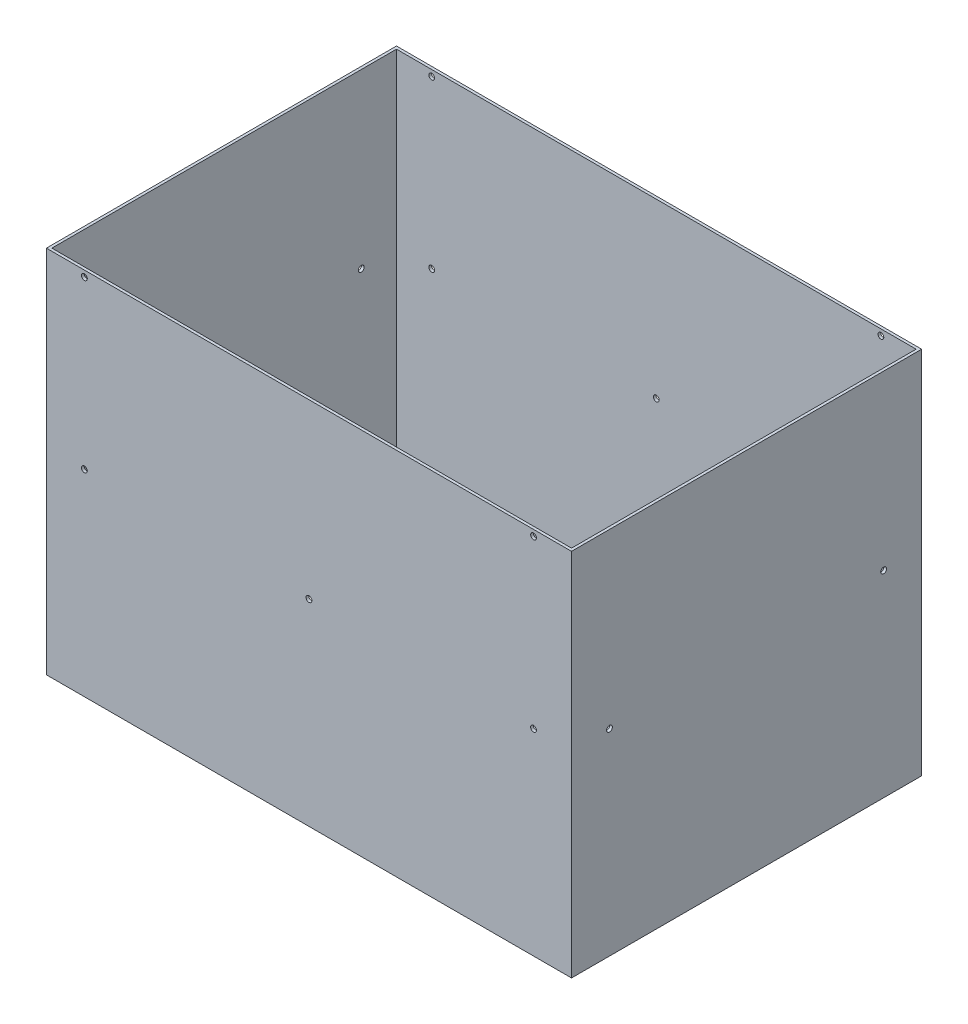
SolidWorks part; units mm, degrees
ref_plane "Alzado" through (0, 0, 0) normal (0, 0, 1) x (1, 0, 0)
ref_plane "Planta" through (0, 0, 0) normal (0, 1, 0) x (1, 0, 0)
ref_plane "Vista lateral" through (0, 0, 0) normal (1, 0, 0) x (0, 0, -1)
sketch "Croquis1" plane through (0, 0, 0) normal (0, 0, 1) x (1, 0, 0)
  line L0 (-135, -46.6) -> (135, -46.6)
  line L1 (0, -55) -> (0, 55) construction
  line L2 (-135, -46.6) -> (-135, 143.4)
  line L3 (135, -46.6) -> (135, 143.4)
  line L4 (-135, 143.4) -> (135, 143.4)
  line L9 (55, 0) -> (-55, 0) construction
  point P2 (0, -46.6)
  point P5 (-135, 0)
  dimension "D1" = 270
  dimension "D6" = 190
extrude "Saliente-Extruir1" add sketch "Croquis1" along normal mid plane 180
sketch "Croquis2" plane through (0, -46.6, 0) normal (0, 1, 0) x (1, 0, 0)
  line L0 (-55, 0) -> (55, 0) construction
  line L1 (-66, 76) -> (-66, -57)
  line L2 (-66, -57) -> (-126, -57)
  line L3 (-126, -57) -> (-126, 76)
  line L4 (-126, 76) -> (-66, 76)
  line L5 (69.26, 53) -> (69.26, -80)
  line L6 (69.26, -80) -> (129.26, -80)
  line L7 (129.26, -80) -> (129.26, 53)
  line L8 (129.26, 53) -> (69.26, 53)
  line L9 (135, 90) -> (-135, 90) construction
  line L12 (135, -90) -> (-135, -90) construction
  point P1 (67.5, 0)
  point P7 (-66, 76)
  point P9 (-66, -57)
  point P10 (69.26, -80)
  point P13 (69.26, 53)
  point P14 (-68.26, -63.8)
  dimension "D2" = 10
  dimension "D3" = 133
  dimension "D4" = 133
  dimension "D5" = 60
  dimension "D6" = 66
  dimension "D7" = 90
  dimension "D8" = 90
  dimension "D9" = 60
  dimension "D10" = 67.5
  dimension "D11" = 14
extrude "Cortar-Extruir2" cut sketch "Croquis2" against normal mid plane 71.4
sketch "Croquis6" plane through (0, 143.4, 0) normal (0, 1, 0) x (1, 0, 0)
  line L0 (135, 90) -> (-135, 90) construction
  line L1 (-133.6, 88.6) -> (133.6, 88.6)
  line L2 (-133.6, 88.6) -> (-133.6, -88.6)
  line L3 (-133.6, -88.6) -> (133.6, -88.6)
  line L4 (133.6, 88.6) -> (133.6, -88.6)
  line L5 (-135, -90) -> (-135, 90) construction
  line L6 (135, -90) -> (135, 90) construction
  line L7 (135, -90) -> (-135, -90) construction
  dimension "D1" = 1.4
  dimension "D2" = 1.4
  dimension "D3" = 1.4
  dimension "D4" = 1.4
  dimension "D5" = 177.2
extrude "Cortar-Extruir3" cut sketch "Croquis6" against normal blind 188.6
ref_plane "Plano2" through (0, 54.65, 0) normal (0, 1, 0) x (1, 0, 0)
sketch "Croquis8" plane through (0, 0, 90) normal (0, 0, 1) x (1, 0, 0)
  line L0 (123.1006, 54.65) -> (-123.1006, 54.65) construction
  line L1 (-135, 143.4) -> (-135, -46.6) construction
  line L2 (-135, 54.65) -> (135, 54.65) construction
  line L3 (135, -46.6) -> (135, 143.4) construction
  circle A0 centre (-115.475, 54.65) radius 1.5
  circle A1 centre (0, 54.65) radius 1.5
  circle A2 centre (115.475, 54.65) radius 1.5
  point P0 (-135, 54.65)
  point P5 (-135, 54.65)
  point P10 (-115.475, 54.65)
  point P11 (0, 54.65)
  point P12 (115.475, 54.65)
  dimension "D1" = 0
  dimension "D2" = 19.525
  dimension "D4" = 19.525
extrude "Cortar-Extruir4" cut sketch "Croquis8" against normal mid plane 600
sketch "Croquis10" plane through (-135, 0, 0) normal (-1, 0, 0) x (0, 0, 1)
  line L2 (90, 143.4) -> (90, -46.6) construction
  line L9 (-90, 143.4) -> (-90, -46.6) construction
  line L10 (123.1006, 54.65) -> (-123.1006, 54.65) construction
  line L11 (-90, 54.65) -> (90, 54.65) construction
  circle A0 centre (-70.475, 54.65) radius 1.5
  circle A1 centre (70.475, 54.65) radius 1.5
  point P0 (-90, 54.65)
  point P1 (-70.475, 54.65)
  point P4 (70.475, 54.65)
  dimension "D1" = 19.525
  dimension "D2" = 19.525
extrude "Cortar-Extruir6" cut sketch "Croquis10" against normal blind 368 and the other way blind 135
sketch "Croquis11" plane through (0, 0, 90) normal (0, 0, 1) x (1, 0, 0)
  line L0 (-115.475, 54.65) -> (-115.475, 143.4) construction
  line L1 (135, 143.4) -> (-135, 143.4) construction
  line L2 (115.475, 54.65) -> (115.475, 143.4) construction
  line L4 (-135, 143.4) -> (-135, -46.6) construction
  circle A0 centre (-115.475, 140.275) radius 1.5
  circle A1 centre (115.475, 140.275) radius 1.5
  point P10 (-115.475, 140.275)
  point P11 (115.475, 140.275)
  dimension "D3" = 19.525
  dimension "D1" = 3.125
  dimension "D2" = 3.125
extrude "Cortar-Extruir7" cut sketch "Croquis11" against normal blind 260.1 and the other way blind 112
